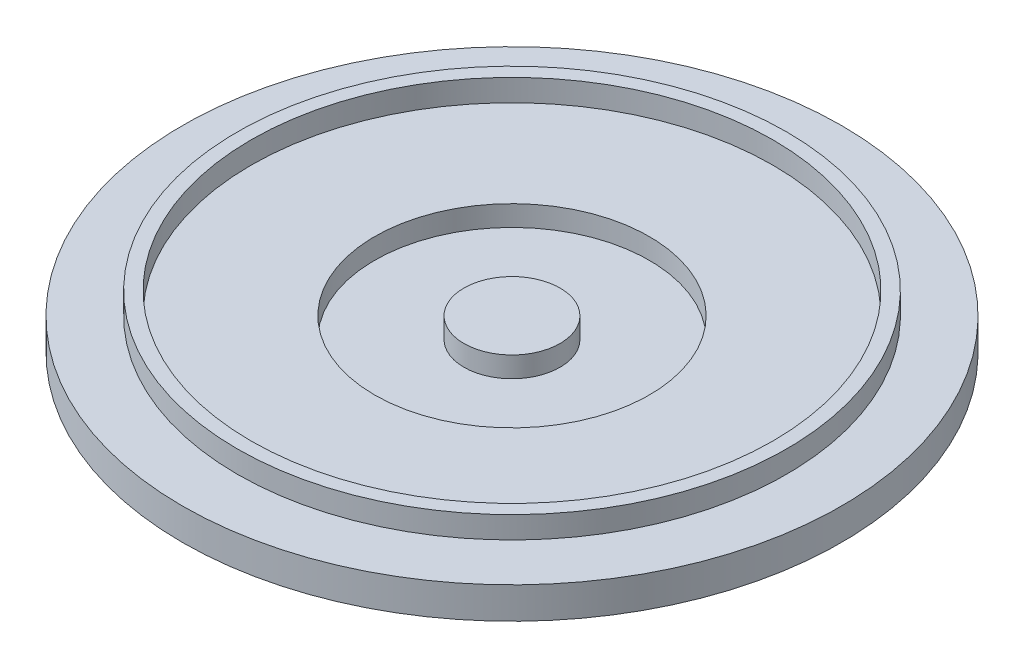
SolidWorks part; units mm, degrees
ref_plane "Front Plane" through (0, 0, 0) normal (0, 0, 1) x (1, 0, 0)
ref_plane "Top Plane" through (0, 0, 0) normal (0, 1, 0) x (1, 0, 0)
ref_plane "Right Plane" through (0, 0, 0) normal (1, 0, 0) x (0, 0, -1)
sketch "Sketch1" plane through (0, 0, 0) normal (0, 1, 0) x (1, 0, 0)
  circle A0 centre (0, 0) radius 24
  dimension "D1" = 48
extrude "Boss-Extrude1" add sketch "Sketch1" along normal blind 2.3
sketch "Sketch2" plane through (0, 2.3, 0) normal (0, 1, 0) x (1, 0, 0)
  circle A4 centre (0, 0) radius 10
  circle A5 centre (0, 0) radius 3.5
  dimension "D1" = 20
  dimension "D2" = 7
extrude "Cut-Extrude1" cut sketch "Sketch2" against normal blind 1.5
sketch "Sketch3" plane through (0, 2.3, 0) normal (0, 1, 0) x (1, 0, 0)
  circle A0 centre (0, 0) radius 19
  circle A1 centre (0, 0) radius 20
  dimension "D1" = 38
  dimension "D2" = 40
extrude "Boss-Extrude2" add sketch "Sketch3" along normal blind 1.6
